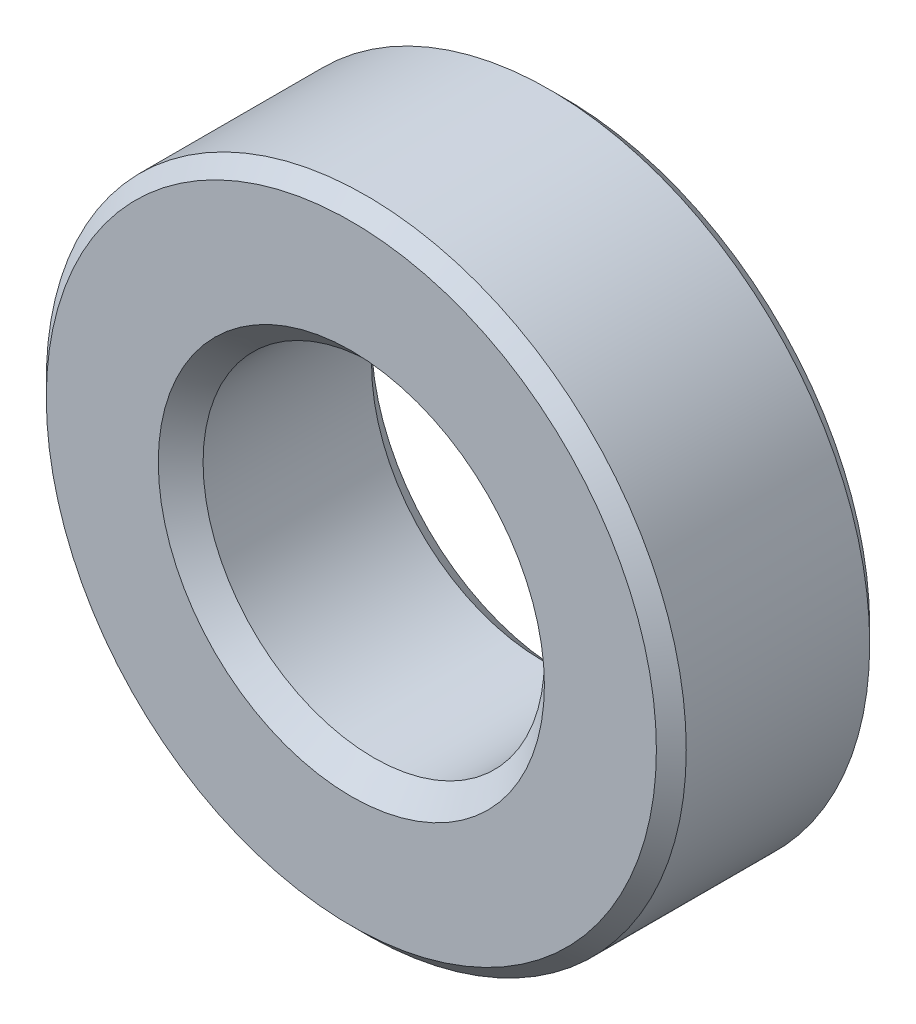
SolidWorks part; units mm, degrees
ref_plane "Front Plane" through (0, 0, 0) normal (0, 0, 1) x (1, 0, 0)
ref_plane "Top Plane" through (0, 0, 0) normal (0, 1, 0) x (1, 0, 0)
ref_plane "Right Plane" through (0, 0, 0) normal (1, 0, 0) x (0, 0, -1)
sketch "Sketch1" plane through (0, 0, 0) normal (0, 0, 1) x (1, 0, 0)
  circle A0 centre (0, 0) radius 3 construction
  circle A1 centre (0, 0) radius 1.6 construction
  point P4 (0, 3)
  dimension "ID" = 3.2
  dimension "OD" = 6
sketch "Sketch2" plane through (0, 0, 0) normal (1, 0, 0) x (0, 0, -1)
  line L0 (-1, 3) -> (1, 3) construction
  dimension "Length" = 2
sketch "Sketch3" plane through (0, 0, 0) normal (0, 0, 1) x (1, 0, 0)
  circle A0 centre (0, 0) radius 1.6 construction
  circle A1 centre (0, 0) radius 3 construction
  circle A2 centre (0, 0) radius 1.6
  circle A3 centre (0, 0) radius 3
extrude "Boss-Extrude1" add sketch "Sketch3" against normal up to vertex (1 mm away) and the other way up to vertex (1 mm away) up to point (0, 3, -1) other way up to point (0, 3, 1)
chamfer "Chamfer1" distance 0.14 angle 45 2 edges at (3, 0, 1) (3, 0, -1)
chamfer "Chamfer2" distance 0.21 angle 45 2 edges at (1.6, 0, 1) (1.6, 0, -1)
equation "\"D1@Chamfer1\"=(\"OD@Sketch1\"-\"ID@Sketch1\")*0.05"
equation "\"D1@Chamfer2\"=(\"OD@Sketch1\"-\"ID@Sketch1\")*0.075"
